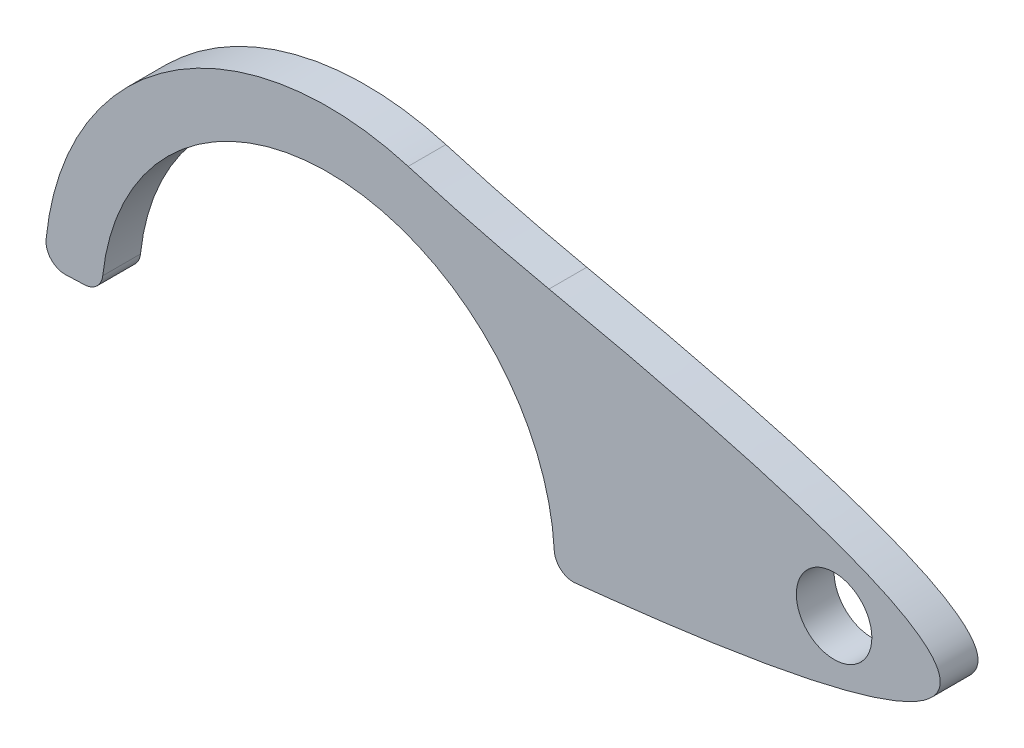
SolidWorks part; units mm, degrees
ref_plane "Plan de face" through (0, 0, 0) normal (0, 0, 1) x (1, 0, 0)
ref_plane "Plan de dessus" through (0, 0, 0) normal (0, 1, 0) x (1, 0, 0)
ref_plane "Plan de droite" through (0, 0, 0) normal (1, 0, 0) x (0, 0, -1)
sketch "Esquisse1" plane through (0, 0, 0) normal (0, 0, 1) x (1, 0, 0)
  line L0 (-14.9969, 0.3065) -> (-11.9927, 0.4197)
  line L1 (11.9927, -0.4197) -> (14.9997, -0.0902)
  arc A0 (11.9927, -0.4197) -> (-11.9927, 0.4197) centre (0, 0) ccw
  arc A1 (14.9997, -0.0902) -> (-14.9969, 0.3065) centre (0, 0) ccw
  circle A2 centre (43.2274, 4.068) radius 2
  circle A3 centre (26.8036, 5.0487) radius 2
  spline S0 degree 2 poles (6.3537, 13.5879) (53.7396, 4.2558) (14.9997, -0.0902) knots 0 0 0 1 1 1
  dimension "D1" = 12
  dimension "D2" = 15
  dimension "D3" = 4
  dimension "D4" = 4
extrude "Boss.-Extru.1" add sketch "Esquisse1" along normal blind 2
fillet "Congé1" radius 1 3 edges at (11.9927, -0.4197, 1) (-11.9927, 0.4197, 1) (-14.9969, 0.3065, 1)
fillet "Congé2" radius 101 1 edges at (6.3537, 13.5879, 1)
